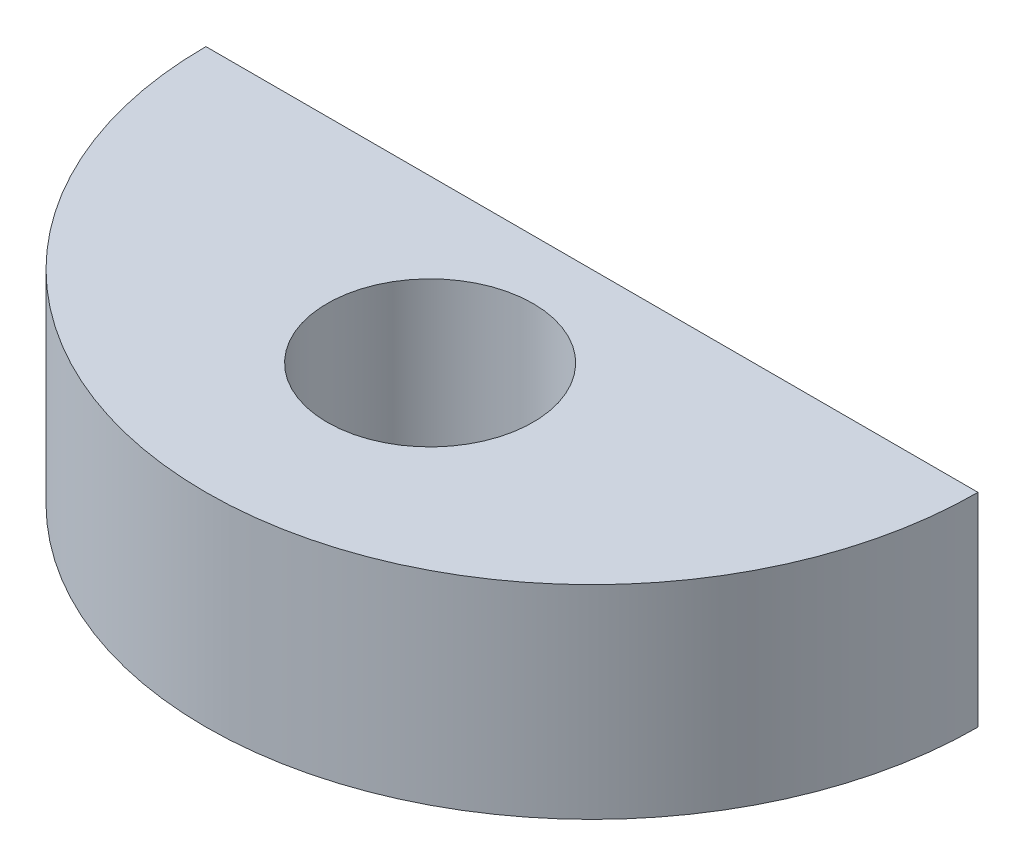
SolidWorks part; units mm, degrees
ref_plane "Front Plane" through (0, 0, 0) normal (0, 0, 1) x (1, 0, 0)
ref_plane "Top Plane" through (0, 0, 0) normal (0, 1, 0) x (1, 0, 0)
ref_plane "Right Plane" through (0, 0, 0) normal (1, 0, 0) x (0, 0, -1)
sketch "Sketch3" plane through (0, 0, 0) normal (0, 1, 0) x (1, 0, 0)
  line L0 (-31.0934, 25.697) -> (45.1066, 25.697)
  circle A0 centre (7.0066, 9.7248) radius 10.16
  arc A1 (-31.0934, 25.697) -> (45.1066, 25.697) centre (7.0066, 25.697) ccw
extrude "Boss-Extrude1" add sketch "Sketch3" along normal blind 20.066
